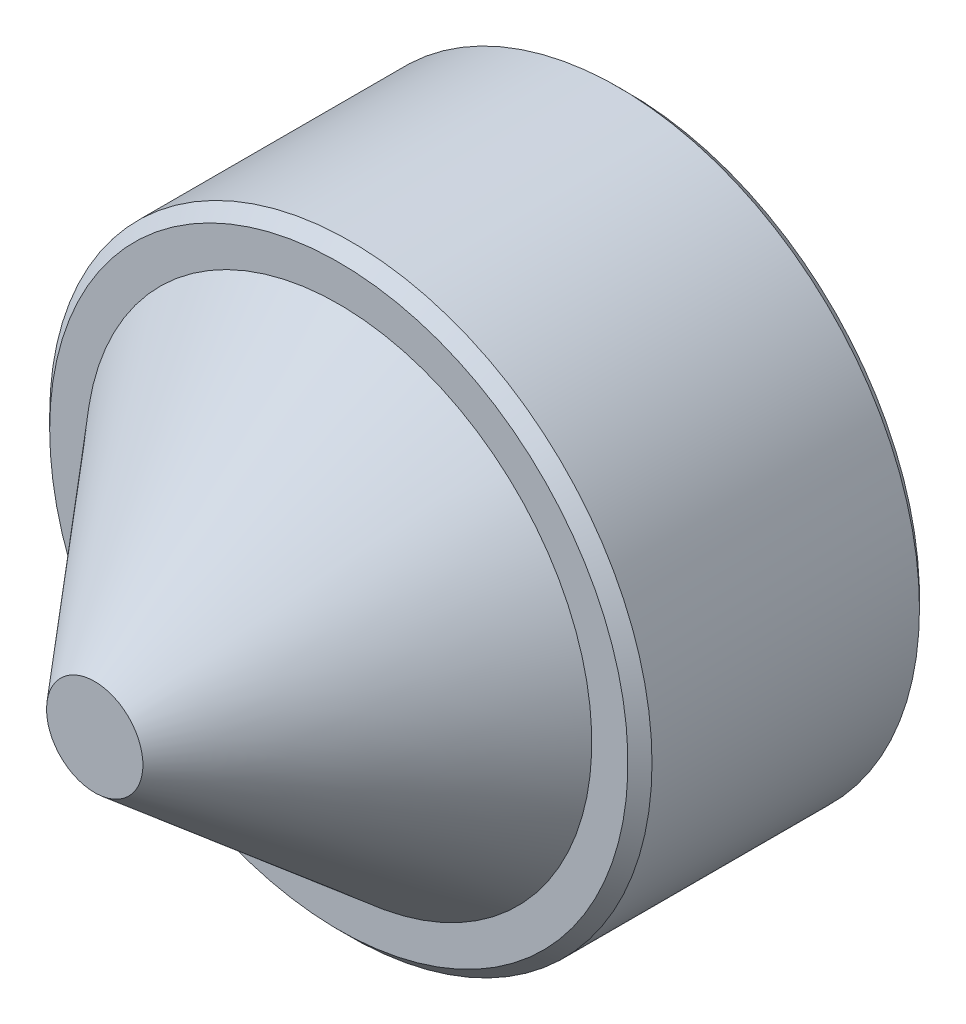
SolidWorks part; units mm, degrees
ref_plane "Front Plane" through (0, 0, 0) normal (0, 0, 1) x (1, 0, 0)
ref_plane "Top Plane" through (0, 0, 0) normal (0, 1, 0) x (1, 0, 0)
ref_plane "Right Plane" through (0, 0, 0) normal (1, 0, 0) x (0, 0, -1)
sketch "body_sketch" plane through (0, 0, 0) normal (0, 1, 0) x (1, 0, 0)
  line L0 (0, 0) -> (12.1, 0)
  line L1 (12.1, 0) -> (12.5, -0.4)
  line L2 (12.5, -0.4) -> (12.5, -11.5)
  line L3 (12.5, -11.5) -> (12, -12)
  line L4 (12, -12) -> (10.5, -12)
  line L5 (10.5, -12) -> (2, -22.13)
  line L6 (2, -22.13) -> (0, -22.13)
  line L7 (0, -22.13) -> (0, 0)
  line L8 (0, 0) -> (0, -32.13) construction
  point P10 (1024, 1024)
  dimension "D1" = 32.13
  dimension "D2" = 12.1
  dimension "D3" = 1024
  dimension "D4" = 1024
  dimension "D5" = 1024.4
  dimension "D6" = 12.5
  dimension "D7" = 1035.5
  dimension "D8" = 12.5
  dimension "D9" = 1036
  dimension "D10" = 12
  dimension "D11" = 1036
  dimension "D12" = 10.5
  dimension "D13" = 1046.13
  dimension "D14" = 2
  dimension "D15" = 1046.13
revolve "body" add sketch "body_sketch" angle 360 about L8
sketch "socket_sketch" plane through (0, 0, 0) normal (0, 1, 0) x (1, 0, 0)
  line L0 (0, 0.5) -> (11.4195, 0.5)
  line L1 (11.4195, 0.5) -> (2.0805, -10.63)
  line L2 (2.0805, -10.63) -> (0, -10.63)
  line L3 (0, -10.63) -> (0, 0.5)
  line L4 (0, 0) -> (0, -20.63) construction
  point P7 (1024, 1024)
  dimension "D1" = 20.63
  dimension "D2" = 0.5
  dimension "D3" = 0.5
  dimension "D4" = 11.4195
  dimension "D5" = 1024
  dimension "D6" = 1024
  dimension "D7" = 1034.63
  dimension "D8" = 2.0805
  dimension "D9" = 1034.63
revolve "socket" cut sketch "socket_sketch" angle 360 about L4
equation "\"D\"= 25mm"
equation "\"HC\"= 12mm"
equation "\"SH\"= 2mm"
equation "\"TIP_D\"= 4mm"
equation "\"CONE_H\"= 10.13mm"
equation "\"CLR\"= 0.5mm"
equation "\"VCLR\"= 0.5mm"
equation "\"CT\"= 0.5mm"
equation "\"CB\"= 0.4mm"
equation "\"SLOPE\"= (((\"D\" / 2) - \"SH\") - (\"TIP_D\" / 2)) / \"CONE_H\""
equation "\"MOUTH_D\"= (\"D\" - (2 * \"SH\")) + (2 * \"CLR\")"
equation "\"SOCK_H\"= \"CONE_H\" + \"VCLR\""
equation "\"ROOF_D\"= \"MOUTH_D\" - ((2 * \"SOCK_H\") * \"SLOPE\")"
equation "\"D2@body_sketch\" = (\"D\" - (2 * \"CB\")) / 2"
equation "\"D5@body_sketch\" = 1024mm + \"CB\""
equation "\"D6@body_sketch\" = \"D\" / 2"
equation "\"D7@body_sketch\" = 1024mm + (\"HC\" - \"CT\")"
equation "\"D8@body_sketch\" = \"D\" / 2"
equation "\"D9@body_sketch\" = 1024mm + \"HC\""
equation "\"D10@body_sketch\" = (\"D\" - (2 * \"CT\")) / 2"
equation "\"D11@body_sketch\" = 1024mm + \"HC\""
equation "\"D12@body_sketch\" = (\"D\" - (2 * \"SH\")) / 2"
equation "\"D13@body_sketch\" = 1024mm + (\"HC\" + \"CONE_H\")"
equation "\"D14@body_sketch\" = \"TIP_D\" / 2"
equation "\"D15@body_sketch\" = 1024mm + (\"HC\" + \"CONE_H\")"
equation "\"D2@socket_sketch\" = abs(-0.5mm)"
equation "\"D3@socket_sketch\" = abs(-0.5mm)"
equation "\"D4@socket_sketch\" = (\"MOUTH_D\" + ((2 * 0.5) * \"SLOPE\")) / 2"
equation "\"D7@socket_sketch\" = 1024mm + \"SOCK_H\""
equation "\"D8@socket_sketch\" = \"ROOF_D\" / 2"
equation "\"D9@socket_sketch\" = 1024mm + \"SOCK_H\""
